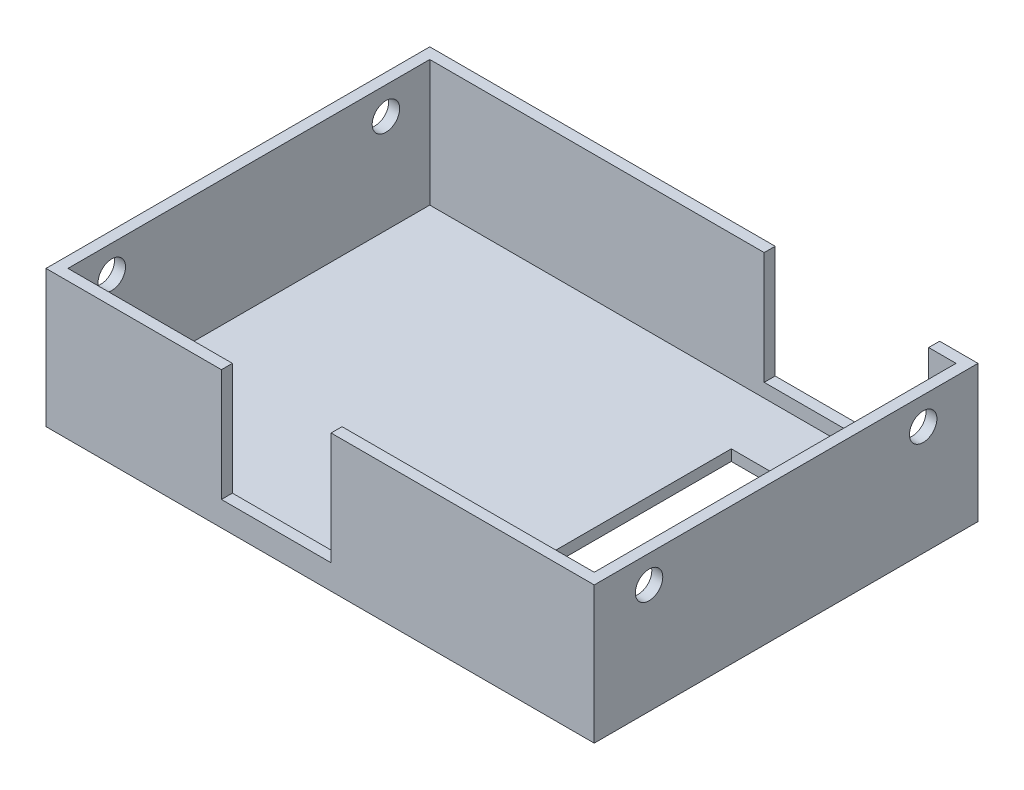
SolidWorks part; units mm, degrees
ref_plane "Front Plane" through (0, 0, 0) normal (0, 0, 1) x (1, 0, 0)
ref_plane "Top Plane" through (0, 0, 0) normal (0, 1, 0) x (1, 0, 0)
ref_plane "Right Plane" through (0, 0, 0) normal (1, 0, 0) x (0, 0, -1)
sketch "Sketch1" plane through (0, 0, 0) normal (0, 1, 0) x (1, 0, 0)
  line L1 (0, 0) -> (127, 0)
  line L2 (0, 0) -> (0, 88.9)
  line L3 (0, 88.9) -> (127, 88.9)
  line L4 (127, 0) -> (127, 88.9)
  dimension "D1" = 127
  dimension "D2" = 88.9
extrude "Boss-Extrude1" add sketch "Sketch1" along normal blind 31.75
shell "Shell1" thickness 2.54
sketch "Sketch3" plane through (127, 0, 0) normal (1, 0, 0) x (0, 0, -1)
  line L0 (0, 31.75) -> (88.9, 31.75) construction
  line L1 (0, 31.75) -> (0, 0) construction
  line L2 (88.9, 31.75) -> (88.9, 0) construction
  circle A0 centre (12.7, 25.4) radius 3.175
  circle A1 centre (76.2, 25.4) radius 3.175
  dimension "D1" = 6.35
  dimension "D6" = 6.35
  dimension "D2" = 6.35
  dimension "D3" = 12.7
  dimension "D4" = 6.35
  dimension "D5" = 12.7
extrude "Cut-Extrude2" cut sketch "Sketch3" against normal blind 31.75
ref_plane "Plane2" through (63.5, 0, 0) normal (1, 0, 0) x (0, 0, -1)
mirror "Mirror2" about plane through (63.5, 0, 0) normal (1, 0, 0) of "Cut-Extrude2"
sketch "Sketch4" plane through (0, 0, -88.9) normal (0, 0, -1) x (-1, 0, 0)
  line L0 (-124.46, 31.75) -> (-124.46, 2.54) construction
  line L1 (-118.11, 31.75) -> (-80.01, 31.75)
  line L2 (-118.11, 31.75) -> (-118.11, 5.715)
  line L3 (-118.11, 5.715) -> (-80.01, 5.715)
  line L4 (-80.01, 31.75) -> (-80.01, 5.715)
  line L5 (-124.46, 2.54) -> (-2.54, 2.54) construction
  line L6 (-124.46, 31.75) -> (-2.54, 31.75) construction
  dimension "D1" = 38.1
  dimension "D2" = 6.35
  dimension "D3" = 3.175
extrude "Cut-Extrude3" cut sketch "Sketch4" against normal blind 2.54
sketch "Sketch5" plane through (0, 0, 0) normal (0, 0, 1) x (1, 0, 0)
  line L1 (40.64, 31.75) -> (66.04, 31.75)
  line L2 (40.64, 31.75) -> (40.64, 5.715)
  line L3 (40.64, 5.715) -> (66.04, 5.715)
  line L4 (66.04, 31.75) -> (66.04, 5.715)
  line L5 (2.54, 2.54) -> (124.46, 2.54) construction
  line L6 (0, 31.75) -> (127, 31.75) construction
  line L7 (2.54, 31.75) -> (2.54, 2.54) construction
  dimension "D1" = 25.4
  dimension "D2" = 38.1
  dimension "D3" = 3.175
extrude "Cut-Extrude4" cut sketch "Sketch5" against normal blind 2.54
sketch "Sketch6" plane through (0, 0, 0) normal (0, -1, 0) x (1, 0, 0)
  line L1 (86.36, -8.89) -> (111.76, -8.89)
  line L2 (86.36, -8.89) -> (86.36, -72.39)
  line L3 (86.36, -72.39) -> (111.76, -72.39)
  line L4 (111.76, -8.89) -> (111.76, -72.39)
  line L5 (2.54, -2.54) -> (124.46, -2.54) construction
  line L6 (124.46, -2.54) -> (124.46, -86.36) construction
  dimension "D1" = 63.5
  dimension "D2" = 25.4
  dimension "D3" = 6.35
  dimension "D4" = 12.7
extrude "Cut-Extrude5" cut sketch "Sketch6" against normal blind 2.54
